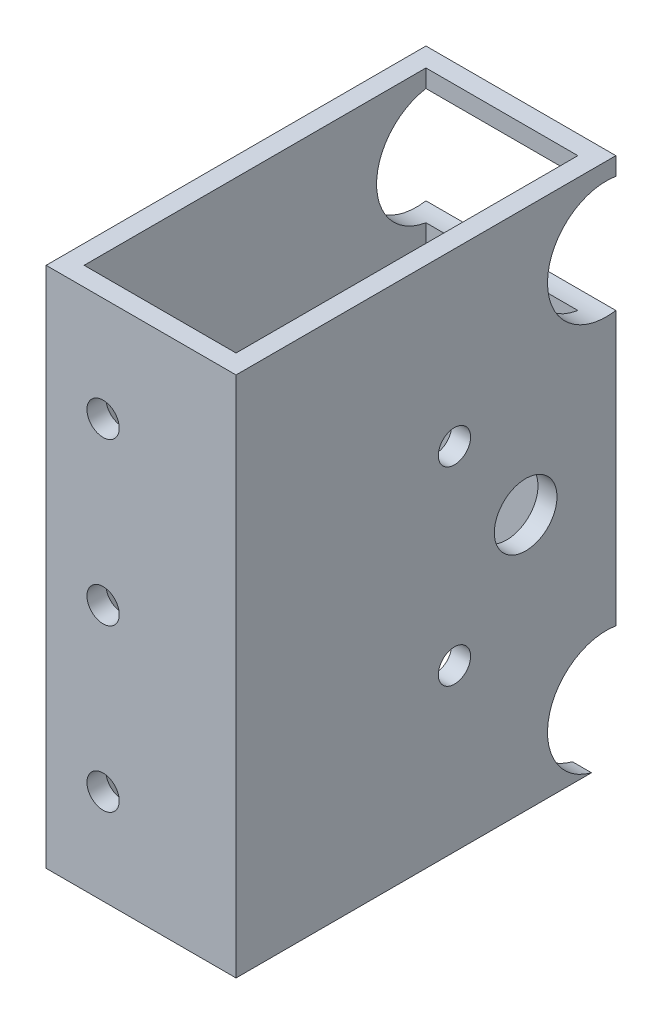
SolidWorks part; units mm, degrees
other "Preload Steel Carriage Core"
ref_plane "Front Plane" through (0, 0, 0) normal (0, 0, 1) x (1, 0, 0)
ref_plane "Top Plane" through (0, 0, 0) normal (0, 1, 0) x (1, 0, 0)
ref_plane "Right Plane" through (0, 0, 0) normal (1, 0, 0) x (0, 0, -1)
sketch3d "Steel tube stock sketch datum points"
  point P0 (29.7083, -56, -29)
  point P1 (39.7083, -56, -29)
  point P2 (29.7083, -46, -29)
ref_plane "Steel tube stock sketch plane" through (0, 0, -29) normal (0, 0, 1) x (1, 0, 0)
sketch "Steel tube stock sketch" plane through (0, 0, -29) normal (0, 0, 1) x (1, 0, 0)
  line L0 (29.7083, -56) -> (49.7083, -56)
  line L1 (49.7083, -56) -> (49.7083, -1)
  line L2 (49.7083, -1) -> (29.7083, -1)
  line L3 (29.7083, -1) -> (29.7083, -56)
extrude "Steel tube stock" add sketch "Steel tube stock sketch" along normal blind 40 separate body
sketch3d "Tube interior sketch datum points"
  point P0 (31.7083, -56.1, -27)
  point P1 (41.7083, -56.1, -27)
  point P2 (31.7083, -46.1, -27)
ref_plane "Tube interior sketch plane" through (0, 0, -27) normal (0, 0, 1) x (1, 0, 0)
sketch "Tube interior sketch" plane through (0, 0, -27) normal (0, 0, 1) x (1, 0, 0)
  line L0 (31.7083, -56.1) -> (47.7083, -56.1)
  line L1 (47.7083, -56.1) -> (47.7083, -0.9)
  line L2 (47.7083, -0.9) -> (31.7083, -0.9)
  line L3 (31.7083, -0.9) -> (31.7083, -56.1)
extrude "Tube interior" cut sketch "Tube interior sketch" along normal blind 36
sketch3d "Guide bush clearance 1 sketch datum points"
  point P0 (29.6, -9, -28)
  point P1 (29.6, 1, -28)
  point P2 (29.6, -9, -18)
ref_plane "Guide bush clearance 1 sketch plane" through (29.6, 0, 0) normal (1, 0, 0) x (0, 0, -1)
sketch "Guide bush clearance 1 sketch" plane through (29.6, 0, 0) normal (1, 0, 0) x (0, 0, -1)
  circle A0 centre (28, -9) radius 6.2
extrude "Guide bush clearance 1" cut sketch "Guide bush clearance 1 sketch" along normal blind 20.3
sketch3d "Guide bush clearance 2 sketch datum points"
  point P0 (29.6, -50, -28)
  point P1 (29.6, -40, -28)
  point P2 (29.6, -50, -18)
ref_plane "Guide bush clearance 2 sketch plane" through (29.6, 0, 0) normal (1, 0, 0) x (0, 0, -1)
sketch "Guide bush clearance 2 sketch" plane through (29.6, 0, 0) normal (1, 0, 0) x (0, 0, -1)
  circle A0 centre (28, -50) radius 6.2
extrude "Guide bush clearance 2" cut sketch "Guide bush clearance 2 sketch" along normal blind 20.3
sketch3d "Screw through clearance sketch datum points"
  point P0 (29.6, -29, -19.5)
  point P1 (29.6, -19, -19.5)
  point P2 (29.6, -29, -9.5)
ref_plane "Screw through clearance sketch plane" through (29.6, 0, 0) normal (1, 0, 0) x (0, 0, -1)
sketch "Screw through clearance sketch" plane through (29.6, 0, 0) normal (1, 0, 0) x (0, 0, -1)
  circle A0 centre (19.5, -29) radius 3.3
extrude "Screw through clearance" cut sketch "Screw through clearance sketch" along normal blind 20.3
sketch3d "Spring pin clearance 1 sketch datum points"
  point P0 (35.7083, -12, 8.9)
  point P1 (45.7083, -12, 8.9)
  point P2 (35.7083, -2, 8.9)
ref_plane "Spring pin clearance 1 sketch plane" through (0, 0, 8.9) normal (0, 0, 1) x (1, 0, 0)
sketch "Spring pin clearance 1 sketch" plane through (0, 0, 8.9) normal (0, 0, 1) x (1, 0, 0)
  circle A0 centre (35.7083, -12) radius 1.7
extrude "Spring pin clearance 1" cut sketch "Spring pin clearance 1 sketch" along normal blind 2.2
sketch3d "Spring pin clearance 2 sketch datum points"
  point P0 (35.7083, -29, 8.9)
  point P1 (45.7083, -29, 8.9)
  point P2 (35.7083, -19, 8.9)
ref_plane "Spring pin clearance 2 sketch plane" through (0, 0, 8.9) normal (0, 0, 1) x (1, 0, 0)
sketch "Spring pin clearance 2 sketch" plane through (0, 0, 8.9) normal (0, 0, 1) x (1, 0, 0)
  circle A0 centre (35.7083, -29) radius 1.7
extrude "Spring pin clearance 2" cut sketch "Spring pin clearance 2 sketch" along normal blind 2.2
sketch3d "Spring pin clearance 3 sketch datum points"
  point P0 (35.7083, -46, 8.9)
  point P1 (45.7083, -46, 8.9)
  point P2 (35.7083, -36, 8.9)
ref_plane "Spring pin clearance 3 sketch plane" through (0, 0, 8.9) normal (0, 0, 1) x (1, 0, 0)
sketch "Spring pin clearance 3 sketch" plane through (0, 0, 8.9) normal (0, 0, 1) x (1, 0, 0)
  circle A0 centre (35.7083, -46) radius 1.7
extrude "Spring pin clearance 3" cut sketch "Spring pin clearance 3 sketch" along normal blind 2.2
sketch3d "Clamp bolt clearance 1 sketch datum points"
  point P0 (47.6, -19, -12)
  point P1 (47.6, -9, -12)
  point P2 (47.6, -19, -2)
ref_plane "Clamp bolt clearance 1 sketch plane" through (47.6, 0, 0) normal (1, 0, 0) x (0, 0, -1)
sketch "Clamp bolt clearance 1 sketch" plane through (47.6, 0, 0) normal (1, 0, 0) x (0, 0, -1)
  circle A0 centre (12, -19) radius 1.7
extrude "Clamp bolt clearance 1" cut sketch "Clamp bolt clearance 1 sketch" along normal blind 2.3
sketch3d "Clamp bolt clearance 2 sketch datum points"
  point P0 (47.6, -39, -12)
  point P1 (47.6, -29, -12)
  point P2 (47.6, -39, -2)
ref_plane "Clamp bolt clearance 2 sketch plane" through (47.6, 0, 0) normal (1, 0, 0) x (0, 0, -1)
sketch "Clamp bolt clearance 2 sketch" plane through (47.6, 0, 0) normal (1, 0, 0) x (0, 0, -1)
  circle A0 centre (12, -39) radius 1.7
extrude "Clamp bolt clearance 2" cut sketch "Clamp bolt clearance 2 sketch" along normal blind 2.3
